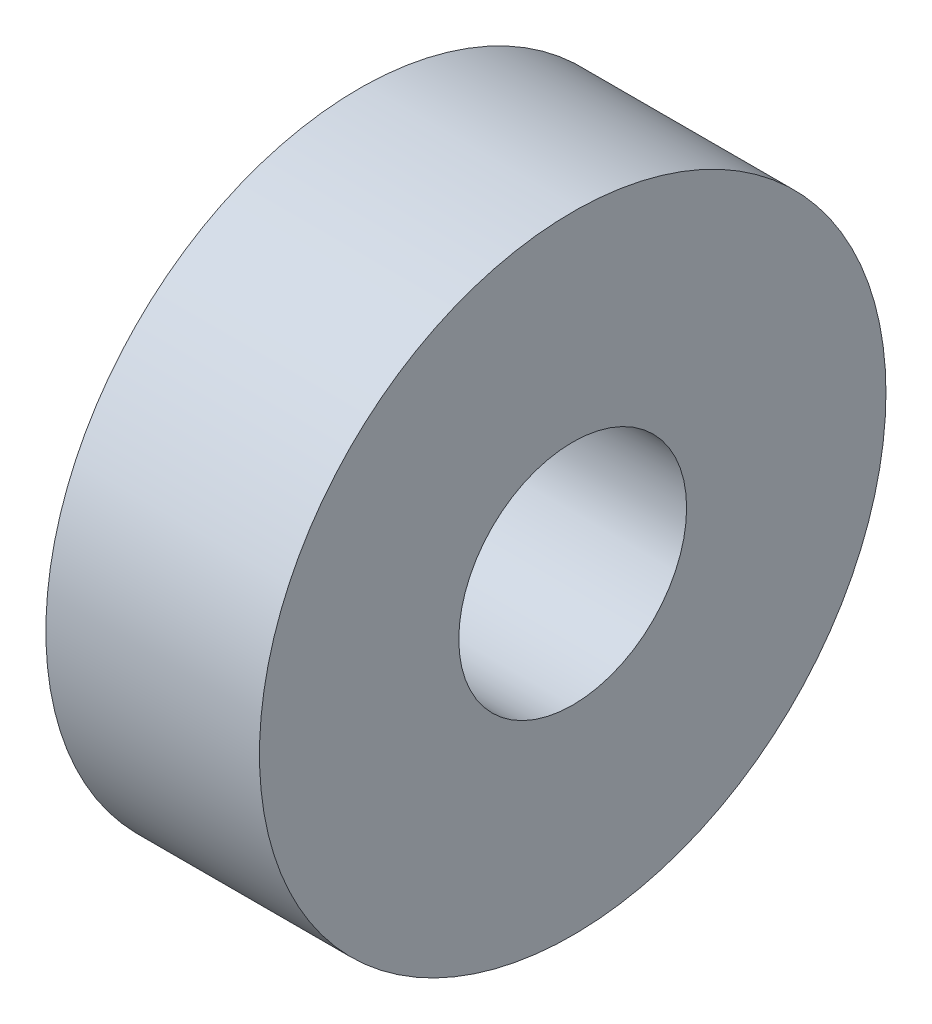
SolidWorks part; units mm, degrees
ref_plane "Front Plane" through (0, 0, 0) normal (0, 0, 1) x (1, 0, 0)
ref_plane "Top Plane" through (0, 0, 0) normal (0, 1, 0) x (1, 0, 0)
ref_plane "Right Plane" through (0, 0, 0) normal (1, 0, 0) x (0, 0, -1)
sketch "Sketch1" plane through (0, 0, 0) normal (1, 0, 0) x (0, 0, -1)
  circle A0 centre (0, 0) radius 4
  circle A1 centre (0, 0) radius 11
  dimension "D1" = 8
  dimension "D2" = 22
extrude "Boss-Extrude1" add sketch "Sketch1" along normal blind 7.5
